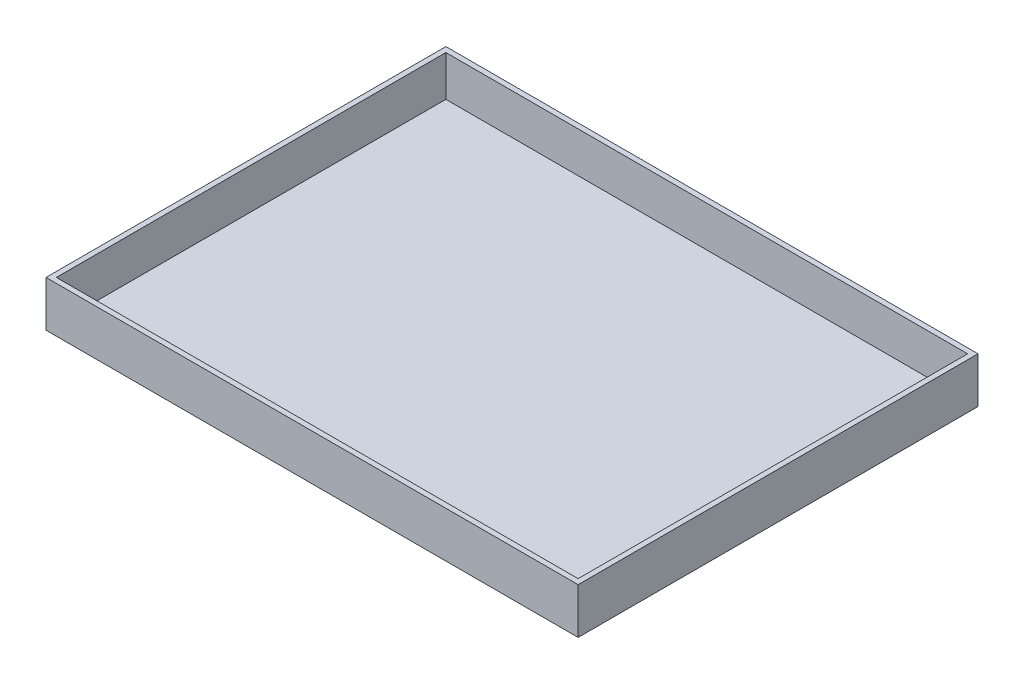
SolidWorks part; units mm, degrees
ref_plane "Front Plane" through (0, 0, 0) normal (0, 0, 1) x (1, 0, 0)
ref_plane "Top Plane" through (0, 0, 0) normal (0, 1, 0) x (1, 0, 0)
ref_plane "Right Plane" through (0, 0, 0) normal (1, 0, 0) x (0, 0, -1)
sketch "Sketch1" plane through (0, 0, 0) normal (0, 1, 0) x (1, 0, 0)
  line L1 (-1307.5, -982.5) -> (1307.5, -982.5)
  line L2 (-1307.5, -982.5) -> (-1307.5, 982.5)
  line L3 (-1307.5, 982.5) -> (1307.5, 982.5)
  line L4 (1307.5, -982.5) -> (1307.5, 982.5)
  line L5 (-1307.5, -982.5) -> (1307.5, 982.5) construction
  line L6 (-1307.5, 982.5) -> (1307.5, -982.5) construction
  point P0 (0, 0)
  dimension "D1" = 1965
  dimension "D2" = 2615
extrude "Boss-Extrude1" add sketch "Sketch1" along normal blind 260
shell "Shell1" thickness 25.4
sketch "Sketch2" plane through (0, 260, 0) normal (0, 1, 0) x (1, 0, 0)
  line L1 (1307.5, -982.5) -> (-1307.5, -982.5)
  line L2 (1307.5, -982.5) -> (1307.5, 982.5)
  line L3 (1307.5, 982.5) -> (-1307.5, 982.5)
  line L4 (-1307.5, -982.5) -> (-1307.5, 982.5)
  line L5 (1307.5, -982.5) -> (-1307.5, 982.5) construction
  line L6 (1307.5, 982.5) -> (-1307.5, -982.5) construction
  point P0 (0, 0)
extrude "Cut-Extrude1" cut sketch "Sketch2" against normal blind 35.306
